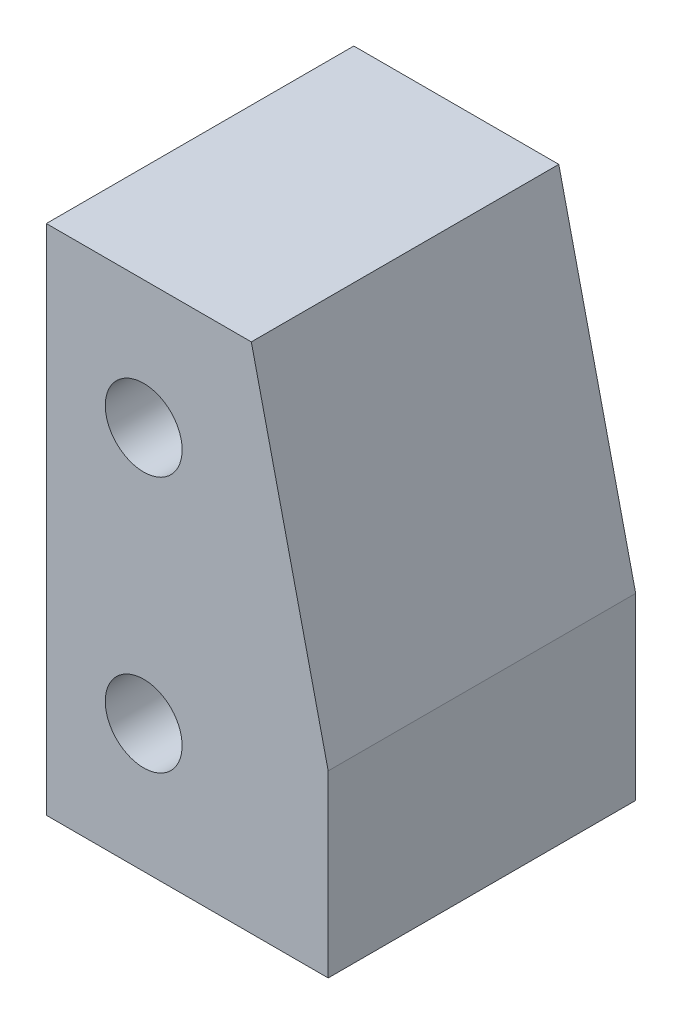
SolidWorks part; units mm, degrees
ref_plane "前视基准面" through (0, 0, 0) normal (0, 0, 1) x (1, 0, 0)
ref_plane "上视基准面" through (0, 0, 0) normal (0, 1, 0) x (1, 0, 0)
ref_plane "右视基准面" through (0, 0, 0) normal (1, 0, 0) x (0, 0, -1)
sketch "草图1" plane through (0, 0, 0) normal (0, 0, 1) x (1, 0, 0)
  line L0 (-996, 10) -> (49004, 10) construction
  line L1 (0, 0) -> (8, 0)
  line L2 (0, 0) -> (0, 20)
  line L3 (0, 20) -> (8, 20)
  line L4 (8, 0) -> (8, 20)
  line L5 (0, 0) -> (8, 20) construction
  line L6 (0, 20) -> (8, 0) construction
  line L7 (3.8, -991.7064) -> (3.8, 49008.2936) construction
  circle A0 centre (3.8, 15) radius 1.5
  circle A1 centre (3.8, 5) radius 1.5
  point P4 (4, 10)
  dimension "D3" = 3
  dimension "D1" = 20
  dimension "D2" = 8
  dimension "D4" = 5
  dimension "D5" = 3.8
extrude "凸台-拉伸1" add sketch "草图1" along normal blind 12
sketch "草图2" plane through (0, 0, 12) normal (0, 0, 1) x (1, 0, 0)
  line L0 (8, 20) -> (11, 7)
  line L1 (11, 7) -> (11, 0)
  line L2 (11, 0) -> (8, 0)
  line L3 (8, 20) -> (8, 0)
  dimension "D1" = 3
  dimension "D2" = 7
extrude "凸台-拉伸2" add sketch "草图2" against normal up to surface (12 mm away) up to face at (5.3, 15, 0)
sketch "草图3" plane through (0, 0, 0) normal (0, -1, 0) x (1, 0, 0)
  line L0 (8, -988) -> (8, 49012) construction
  line L2 (11, 0) -> (11, 12) construction
  line L3 (-989.5, 6) -> (49010.5, 6) construction
  circle A0 centre (8, 6) radius 1.25
  point P7 (11, 6)
  dimension "D2" = 2.5
  dimension "D1" = 3
extrude "切除-拉伸1" cut sketch "草图3" against normal blind 7 and the other way through all
